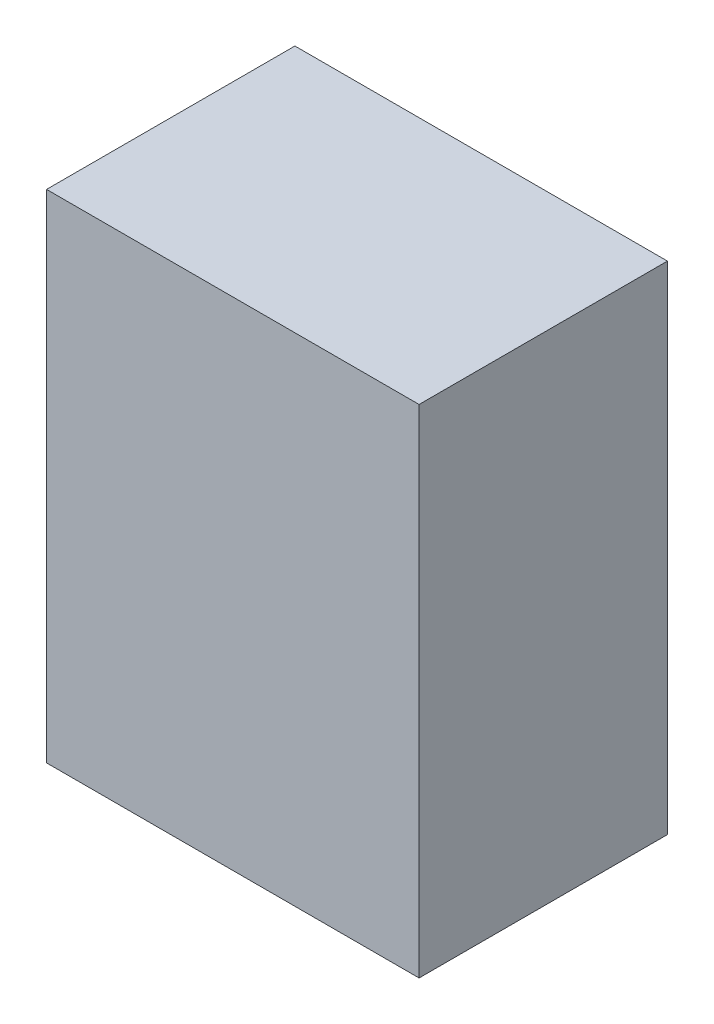
SolidWorks part; units mm, degrees
ref_plane "Front Plane" through (0, 0, 0) normal (0, 0, 1) x (1, 0, 0)
ref_plane "Top Plane" through (0, 0, 0) normal (0, 1, 0) x (1, 0, 0)
ref_plane "Right Plane" through (0, 0, 0) normal (1, 0, 0) x (0, 0, -1)
sketch "ｽｹｯﾁ1" plane through (0, 0, 0) normal (0, 0, 1) x (1, 0, 0)
  line L1 (-30, -40) -> (30, -40)
  line L2 (-30, -40) -> (-30, 40)
  line L3 (-30, 40) -> (30, 40)
  line L4 (30, -40) -> (30, 40)
  line L5 (-30, -40) -> (30, 40) construction
  line L6 (-30, 40) -> (30, -40) construction
  point P0 (0, 0)
  dimension "D1" = 60
  dimension "D2" = 80
extrude "ﾎﾞｽ - 押し出し1" add sketch "ｽｹｯﾁ1" along normal mid plane 40
equation "\"8－\"=40.4046"
